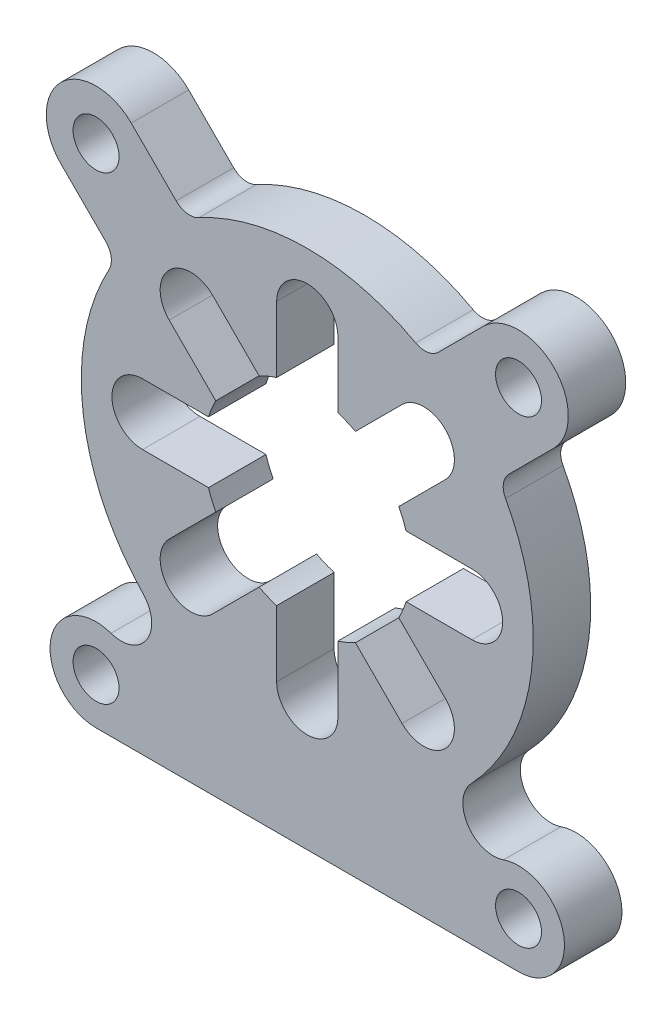
SolidWorks part; units mm, degrees
ref_plane "Alzado" through (0, 0, 0) normal (0, 0, 1) x (1, 0, 0)
ref_plane "Planta" through (0, 0, 0) normal (0, 1, 0) x (1, 0, 0)
ref_plane "Vista lateral" through (0, 0, 0) normal (1, 0, 0) x (0, 0, -1)
sketch "Croquis1" plane through (0, 0, 0) normal (0, 0, 1) x (1, 0, 0)
  line L0 (-55.1543, 55.1543) -> (0, 0) construction
  line L1 (0, 97.1502) -> (0, -96.8972) construction
  line L2 (-64.3467, 45.9619) -> (-52.6205, 34.2357)
  line L3 (-45.9619, 64.3467) -> (-34.2357, 52.6205)
  line L4 (-55.1543, -77) -> (55.1543, -77)
  line L5 (45.9619, 64.3467) -> (34.2357, 52.6205)
  line L6 (64.3467, 45.9619) -> (52.6205, 34.2357)
  arc A0 (-51.7688, 28.3017) -> (-42.8161, -40.5928) centre (0, 0) ccw
  arc A1 (-45.9619, 64.3467) -> (-64.3467, 45.9619) centre (-55.1543, 55.1543) ccw
  arc A2 (28.3017, 51.7688) -> (-28.3017, 51.7688) centre (0, 0) ccw
  circle A3 centre (0, 0) radius 78 construction
  arc A4 (-34.2357, 52.6205) -> (-28.3017, 51.7688) centre (-30.7002, 56.156) ccw
  arc A5 (-52.6205, 34.2357) -> (-51.7688, 28.3017) centre (-56.156, 30.7002) cw
  arc A6 (-51.2348, -53.6582) -> (-55.1543, -77) centre (-55.1543, -65) ccw
  arc A7 (-51.2348, -53.6582) -> (-42.8161, -40.5928) centre (-48.6217, -46.097) ccw
  arc A8 (51.2348, -53.6582) -> (42.8161, -40.5928) centre (48.6217, -46.097) cw
  arc A9 (51.2348, -53.6582) -> (55.1543, -77) centre (55.1543, -65) cw
  arc A10 (52.6205, 34.2357) -> (51.7688, 28.3017) centre (56.156, 30.7002) ccw
  arc A11 (34.2357, 52.6205) -> (28.3017, 51.7688) centre (30.7002, 56.156) cw
  arc A12 (45.9619, 64.3467) -> (64.3467, 45.9619) centre (55.1543, 55.1543) cw
  arc A13 (42.8161, -40.5928) -> (51.7688, 28.3017) centre (0, 0) ccw
  point P18 (0, 0)
  point P25 (0, -77)
  dimension "D1" = 118
  dimension "D3" = 13
  dimension "D4" = 156
  dimension "D5" = 5
  dimension "D6" = 5
  dimension "D7" = 8
  dimension "D8" = 12
  dimension "D2" = 45
  dimension "D9" = 65
extrude "Saliente-Extruir1" add sketch "Croquis1" along normal blind 15
sketch "Croquis2" plane through (0, 0, 15) normal (0, 0, 1) x (1, 0, 0)
  line L0 (0, 80.1868) -> (0, -80.1868) construction
  line L1 (-8, 43) -> (-8, 25.7876)
  line L2 (8, 43) -> (8, 25.7876)
  line L3 (36.0624, 24.7487) -> (23.8914, 12.5777)
  line L4 (24.7487, 36.0624) -> (12.5777, 23.8914)
  line L5 (-34.2357, 52.6205) -> (-45.9619, 64.3467)
  line L6 (-64.3467, 45.9619) -> (-52.6205, 34.2357)
  line L7 (-55.1543, -77) -> (55.1543, -77)
  line L8 (52.6205, 34.2357) -> (64.3467, 45.9619)
  line L9 (45.9619, 64.3467) -> (34.2357, 52.6205)
  line L10 (-34.2357, 52.6205) -> (-45.9619, 64.3467)
  line L11 (-64.3467, 45.9619) -> (-52.6205, 34.2357)
  line L12 (-55.1543, -77) -> (55.1543, -77)
  line L13 (52.6205, 34.2357) -> (64.3467, 45.9619)
  line L14 (45.9619, 64.3467) -> (34.2357, 52.6205)
  line L15 (43, -8) -> (25.7876, -8)
  line L16 (43, 8) -> (25.7876, 8)
  line L17 (24.7487, -36.0624) -> (12.5777, -23.8914)
  line L18 (36.0624, -24.7487) -> (23.8914, -12.5777)
  line L19 (-8, -43) -> (-8, -25.7876)
  line L20 (8, -43) -> (8, -25.7876)
  line L21 (-36.0624, -24.7487) -> (-23.8914, -12.5777)
  line L22 (-24.7487, -36.0624) -> (-12.5777, -23.8914)
  line L23 (-43, 8) -> (-25.7876, 8)
  line L24 (-43, -8) -> (-25.7876, -8)
  line L25 (-24.7487, 36.0624) -> (-12.5777, 23.8914)
  line L26 (-36.0624, 24.7487) -> (-23.8914, 12.5777)
  circle A0 centre (-55.1543, 55.1543) radius 6
  circle A1 centre (55.1543, 55.1543) radius 6
  circle A2 centre (-55.1543, -65) radius 6
  circle A3 centre (55.1543, -65) radius 6
  arc A4 (-8, 25.7876) -> (-12.5777, 23.8914) centre (0, 0) ccw
  circle A5 centre (0, 0) radius 43 construction
  arc A6 (8, 43) -> (-8, 43) centre (0, 43) ccw
  arc A7 (36.0624, 24.7487) -> (24.7487, 36.0624) centre (30.4056, 30.4056) ccw
  arc A8 (43, -8) -> (43, 8) centre (43, 0) ccw
  arc A9 (24.7487, -36.0624) -> (36.0624, -24.7487) centre (30.4056, -30.4056) ccw
  arc A10 (-8, -43) -> (8, -43) centre (0, -43) ccw
  arc A11 (-36.0624, -24.7487) -> (-24.7487, -36.0624) centre (-30.4056, -30.4056) ccw
  arc A12 (-43, 8) -> (-43, -8) centre (-43, 0) ccw
  arc A13 (28.3017, 51.7688) -> (34.2357, 52.6205) centre (30.7002, 56.156) ccw
  arc A14 (28.3017, 51.7688) -> (-28.3017, 51.7688) centre (0, 0) ccw
  arc A15 (-34.2357, 52.6205) -> (-28.3017, 51.7688) centre (-30.7002, 56.156) ccw
  arc A16 (-45.9619, 64.3467) -> (-64.3467, 45.9619) centre (-55.1543, 55.1543) ccw
  arc A17 (-51.7688, 28.3017) -> (-52.6205, 34.2357) centre (-56.156, 30.7002) ccw
  arc A18 (-51.7688, 28.3017) -> (-42.8161, -40.5928) centre (0, 0) ccw
  arc A19 (-51.2348, -53.6582) -> (-42.8161, -40.5928) centre (-48.6217, -46.097) ccw
  arc A20 (-51.2348, -53.6582) -> (-55.1543, -77) centre (-55.1543, -65) ccw
  arc A21 (55.1543, -77) -> (51.2348, -53.6582) centre (55.1543, -65) ccw
  arc A22 (42.8161, -40.5928) -> (51.2348, -53.6582) centre (48.6217, -46.097) ccw
  arc A23 (42.8161, -40.5928) -> (51.7688, 28.3017) centre (0, 0) ccw
  arc A24 (52.6205, 34.2357) -> (51.7688, 28.3017) centre (56.156, 30.7002) ccw
  arc A25 (64.3467, 45.9619) -> (45.9619, 64.3467) centre (55.1543, 55.1543) ccw
  arc A26 (28.3017, 51.7688) -> (34.2357, 52.6205) centre (30.7002, 56.156) ccw
  arc A27 (28.3017, 51.7688) -> (-28.3017, 51.7688) centre (0, 0) ccw
  arc A28 (-34.2357, 52.6205) -> (-28.3017, 51.7688) centre (-30.7002, 56.156) ccw
  arc A29 (-45.9619, 64.3467) -> (-64.3467, 45.9619) centre (-55.1543, 55.1543) ccw
  arc A30 (-51.7688, 28.3017) -> (-52.6205, 34.2357) centre (-56.156, 30.7002) ccw
  arc A31 (-51.7688, 28.3017) -> (-42.8161, -40.5928) centre (0, 0) ccw
  arc A32 (-51.2348, -53.6582) -> (-42.8161, -40.5928) centre (-48.6217, -46.097) ccw
  arc A33 (-51.2348, -53.6582) -> (-55.1543, -77) centre (-55.1543, -65) ccw
  arc A34 (55.1543, -77) -> (51.2348, -53.6582) centre (55.1543, -65) ccw
  arc A35 (42.8161, -40.5928) -> (51.2348, -53.6582) centre (48.6217, -46.097) ccw
  arc A36 (42.8161, -40.5928) -> (51.7688, 28.3017) centre (0, 0) ccw
  arc A37 (52.6205, 34.2357) -> (51.7688, 28.3017) centre (56.156, 30.7002) ccw
  arc A38 (64.3467, 45.9619) -> (45.9619, 64.3467) centre (55.1543, 55.1543) ccw
  arc A39 (-24.7487, 36.0624) -> (-36.0624, 24.7487) centre (-30.4056, 30.4056) ccw
  arc A40 (-23.8914, 12.5777) -> (-25.7876, 8) centre (0, 0) ccw
  arc A41 (12.5777, 23.8914) -> (8, 25.7876) centre (0, 0) ccw
  arc A42 (25.7876, 8) -> (23.8914, 12.5777) centre (0, 0) ccw
  arc A43 (23.8914, -12.5777) -> (25.7876, -8) centre (0, 0) ccw
  arc A44 (8, -25.7876) -> (12.5777, -23.8914) centre (0, 0) ccw
  arc A45 (-12.5777, -23.8914) -> (-8, -25.7876) centre (0, 0) ccw
  arc A46 (-25.7876, -8) -> (-23.8914, -12.5777) centre (0, 0) ccw
  point P36 (0, 0)
  point P83 (0, 0)
  dimension "D2" = 12
  dimension "D3" = 54
  dimension "D4" = 86
  dimension "D5" = 8
  dimension "D1" = 0
  dimension "D6" = 8
extrude "Cortar-Extruir1" cut sketch "Croquis2" against normal through all contours L26 A40 L23 A12 L24 A46 L21 A11 L22 A45 L19 A10 L20 A44 L17 A9 L18 A43 L15 A8 L16 A42 L3 A7 L4 A41 L2 A6 L1 A4 L25 A39 | A1 | A0 | A2 | A3
